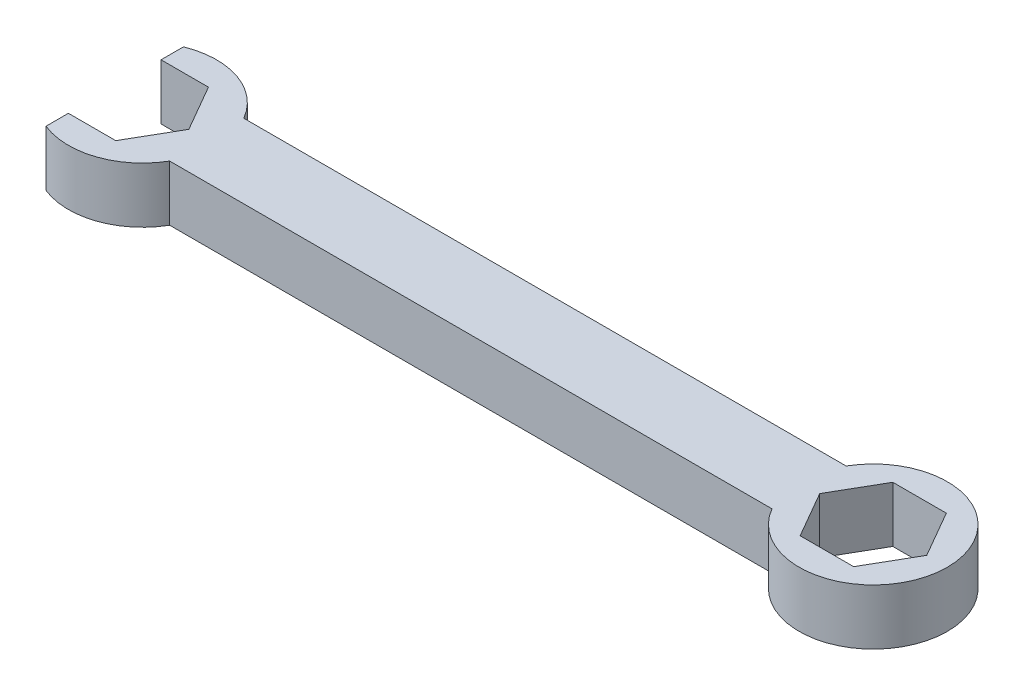
SolidWorks part; units mm, degrees
material "Cast Alloy Steel"
ref_plane "Front Plane" through (0, 0, 0) normal (0, 0, 1) x (1, 0, 0)
ref_plane "Top Plane" through (0, 0, 0) normal (0, 1, 0) x (1, 0, 0)
ref_plane "Right Plane" through (0, 0, 0) normal (1, 0, 0) x (0, 0, -1)
sketch "Sketch1" plane through (0, 0, 0) normal (0, 1, 0) x (1, 0, 0)
  line L0 (77.4655, 0) -> (70.1332, 0) construction
  line L1 (-13.8833, 5.08) -> (68.6667, 5.08)
  line L2 (-13.8833, -5.08) -> (68.6667, -5.08)
  line L3 (-19.9983, 6.35) -> (-26.4921, 6.35)
  line L4 (70.1332, 0) -> (73.7993, -6.35)
  line L5 (73.7993, -6.35) -> (81.1317, -6.35)
  line L6 (81.1317, -6.35) -> (84.7979, 0)
  line L7 (84.7979, 0) -> (81.1317, 6.35)
  line L8 (81.1317, 6.35) -> (73.7993, 6.35)
  line L9 (73.7993, 6.35) -> (70.1332, 0)
  line L18 (-19.9983, -6.35) -> (-16.3321, 0)
  line L19 (-16.3321, 0) -> (-19.9983, 6.35)
  line L22 (-29.0321, 0) -> (-27.4446, -2.7496) [skipped]
  line L23 (-27.4446, 2.7496) -> (-29.0321, 0) [skipped]
  line L24 (-25.8571, -5.4993) -> (-19.5071, -5.4993) [skipped]
  line L25 (-22.6821, 5.4993) -> (-25.8571, 5.4993) [skipped]
  line L26 (-19.9983, -6.35) -> (-26.4921, -6.35)
  line L27 (-26.4921, 9.4186) -> (-26.4921, 6.35)
  line L29 (-26.4921, -6.35) -> (-26.4921, -9.4186)
  arc A0 (68.6667, -5.08) -> (68.6667, 5.08) centre (77.4655, 0) ccw
  arc A1 (-26.4921, -9.4186) -> (-13.8833, -5.08) centre (-22.6821, 0) ccw
  circle A2 centre (77.4655, 0) radius 6.35 construction
  arc A3 (-13.8833, 5.08) -> (-26.4921, 9.4186) centre (-22.6821, 0) ccw
  dimension "D2" = 20.32
  dimension "D3" = 82.55
  dimension "D1" = 10.16
  dimension "D4" = 12.7
  dimension "D6" = 12.7
  dimension "D7" = 10.16
extrude "Boss-Extrude1" add sketch "Sketch1" along normal blind 7.62
